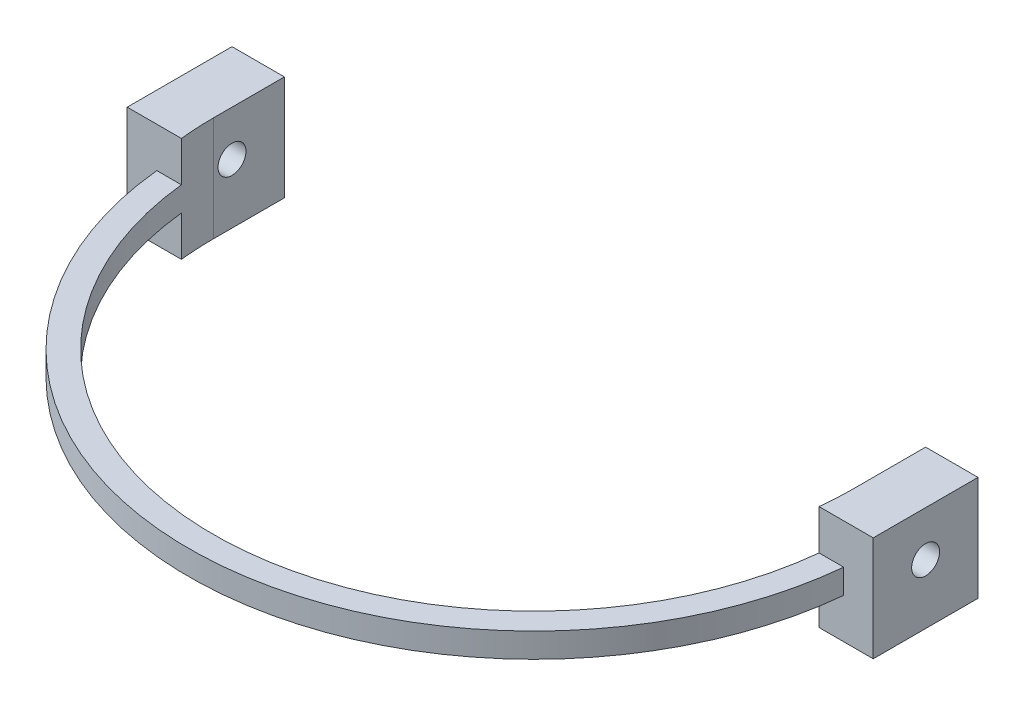
SolidWorks part; units mm, degrees
material "1060 Alloy"
ref_plane "Front Plane" through (0, 0, 0) normal (0, 0, 1) x (1, 0, 0)
ref_plane "Top Plane" through (0, 0, 0) normal (0, 1, 0) x (1, 0, 0)
ref_plane "Right Plane" through (0, 0, 0) normal (1, 0, 0) x (0, 0, -1)
sketch "Sketch1" plane through (0, 0, 0) normal (0, 1, 0) x (1, 0, 0)
  line L0 (-1000, 0) -> (-104.805, 0) construction
  line L1 (0, -1000) -> (0, 49000) construction
  line L2 (106.805, -9.6692) -> (98.3307, -9.6692)
  line L3 (-91.805, 0) -> (91.805, 0)
  line L7 (-106.805, -9.6692) -> (-98.3307, -9.6692)
  line L9 (104.805, 0) -> (49000, 0) construction
  line L10 (-91.805, 0) -> (-91.805, 20.3308)
  line L12 (-91.805, 0) -> (91.805, 0) construction
  line L13 (106.805, 20.3308) -> (106.805, -9.6692)
  line L14 (91.805, 20.3308) -> (106.805, 20.3308)
  line L17 (-91.805, 20.3308) -> (-106.805, 20.3308)
  line L18 (91.805, 0) -> (91.805, 20.3308)
  line L19 (-106.805, 20.3308) -> (-106.805, -9.6692)
  arc A0 (-98.3307, -9.6692) -> (98.3307, -9.6692) centre (0, 0) ccw
  arc A1 (-91.805, 0) -> (91.805, 0) centre (0, 0) ccw
  dimension "D1" = 197.61
  dimension "D2" = 7
  dimension "D3" = 30
  dimension "D4" = 15
extrude "Boss-Extrude1" add sketch "Sketch1" against normal blind 60
ref_plane "Plane4" through (0, 0, 90) normal (0, 0, 1) x (1, 0, 0)
sketch "Sketch30" plane through (0, 0, -20.3308) normal (0, 0, -1) x (-1, 0, 0)
  line L0 (-106.805, -60) -> (-106.805, 0) construction
  line L1 (106.805, 0) -> (-106.805, 0)
  line L2 (106.805, 0) -> (106.805, -30)
  line L3 (106.805, -30) -> (-106.805, -30)
  line L4 (-106.805, 0) -> (-106.805, -30)
  dimension "D1" = 30
extrude "Cut-Extrude19" cut sketch "Sketch30" against normal through all both and the other way through all
sketch "Sketch31" plane through (106.805, 0, 0) normal (1, 0, 0) x (0, 0, -1)
  line L0 (-9.6692, -60) -> (-9.6692, -30) construction
  line L1 (-9.6692, -30) -> (20.3308, -30) construction
  circle A0 centre (5.3308, -42.9267) radius 4
  dimension "D1" = 15
  dimension "D2" = 12.9267
  dimension "D3" = 8
extrude "Cut-Extrude20" cut sketch "Sketch31" against normal through all
sketch "Sketch32" plane through (0, -30, 0) normal (0, 1, 0) x (1, 0, 0)
  line L0 (-106.805, -9.6692) -> (-98.3307, -9.6692) construction
  line L1 (98.3307, -9.6692) -> (-98.3307, -9.6692)
  arc A0 (98.3307, -9.6692) -> (-98.3307, -9.6692) centre (0, 0) cw
extrude "Cut-Extrude21" cut sketch "Sketch32" against normal blind 11.5
sketch "Sketch33" plane through (0, -60, 0) normal (0, -1, 0) x (-1, 0, 0)
  line L0 (98.3307, -9.6692) -> (-98.3307, -9.6692)
  arc A0 (98.3307, -9.6692) -> (-98.3307, -9.6692) centre (0, 0) cw
  arc A1 (-98.3307, -9.6692) -> (98.3307, -9.6692) centre (0, 0) ccw construction
extrude "Cut-Extrude22" cut sketch "Sketch33" against normal blind 11.5
